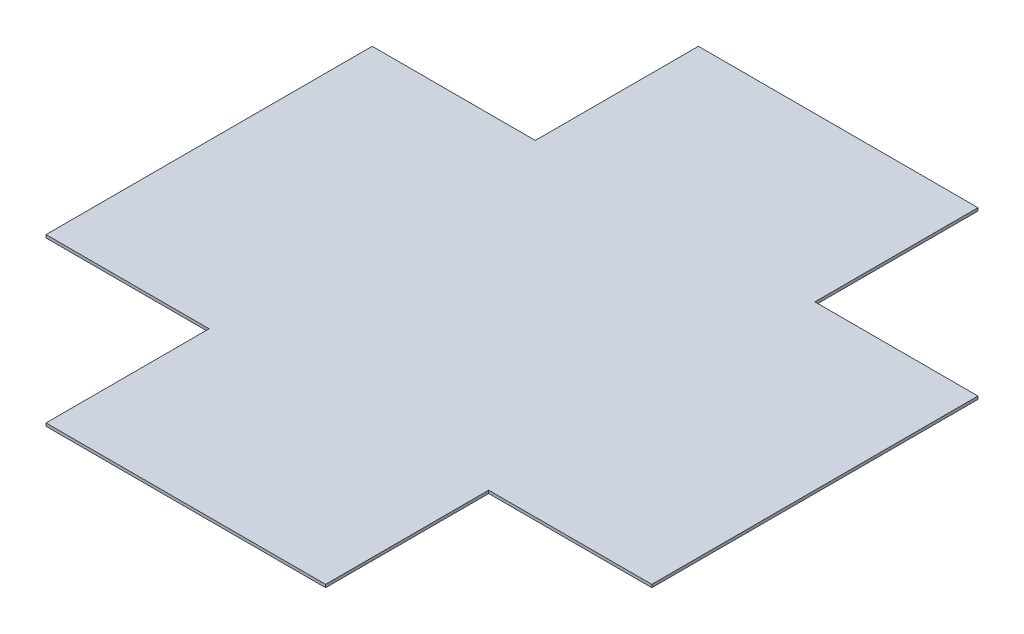
SolidWorks part; units mm, degrees
ref_plane "Front Plane" through (0, 0, 0) normal (0, 0, 1) x (1, 0, 0)
ref_plane "Top Plane" through (0, 0, 0) normal (0, 1, 0) x (1, 0, 0)
ref_plane "Right Plane" through (0, 0, 0) normal (1, 0, 0) x (0, 0, -1)
sketch "Sketch1" plane through (0, 0, 0) normal (0, 1, 0) x (1, 0, 0)
  line L1 (-330.2, 177.8) -> (330.2, 177.8)
  line L2 (-330.2, 177.8) -> (-330.2, -177.8)
  line L3 (-330.2, -177.8) -> (330.2, -177.8)
  line L4 (330.2, 177.8) -> (330.2, -177.8)
  line L5 (-330.2, 177.8) -> (330.2, -177.8) construction
  line L6 (-330.2, -177.8) -> (330.2, 177.8) construction
  line L7 (152.4, -355.6) -> (-152.4, -355.6)
  line L8 (152.4, -355.6) -> (152.4, 355.6)
  line L9 (152.4, 355.6) -> (-152.4, 355.6)
  line L10 (-152.4, -355.6) -> (-152.4, 355.6)
  line L11 (152.4, -355.6) -> (-152.4, 355.6) construction
  line L12 (152.4, 355.6) -> (-152.4, -355.6) construction
  point P0 (0, 0)
  point P6 (0, 0)
  dimension "D1" = 355.6
  dimension "D2" = 660.4
  dimension "D3" = 304.8
  dimension "D4" = 711.2
extrude "Boss-Extrude1" add sketch "Sketch1" along normal mid plane 3.175 contours L3 L10 L1 L2 | L10 L3 L8 L1 | L10 L1 L8 L9 | L10 L7 L8 L3 | L8 L3 L4 L1
